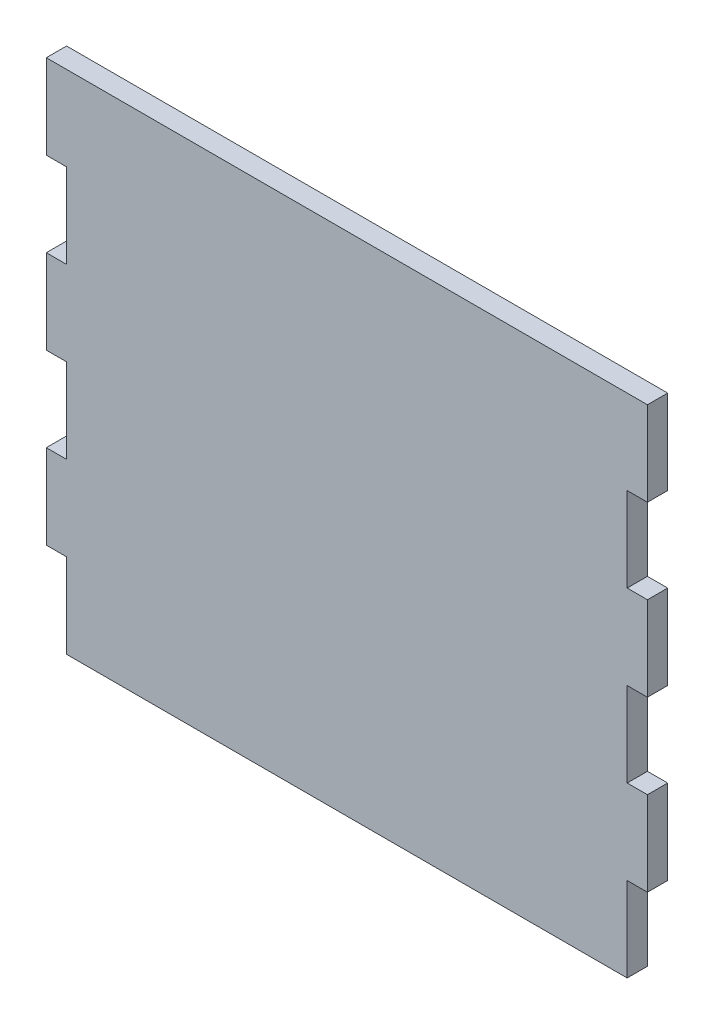
SolidWorks part; units mm, degrees
ref_plane "Front" through (0, 0, 0) normal (0, 0, 1) x (1, 0, 0)
ref_plane "Top" through (0, 0, 0) normal (0, 1, 0) x (1, 0, 0)
ref_plane "Right" through (0, 0, 0) normal (1, 0, 0) x (0, 0, -1)
sketch "Sketch1" plane through (0, 0, 0) normal (0, 0, 1) x (1, 0, 0)
  line L1 (0, 0) -> (-178, 0)
  line L2 (0, 0) -> (0, 150)
  line L3 (0, 150) -> (-178, 150)
  line L4 (-178, 0) -> (-178, 150)
  dimension "D1" = 150
  dimension "D2" = 178
extrude "Boss-Extrude1" add sketch "Sketch1" along normal blind 6
sketch "Sketch2" plane through (0, 0, 6) normal (0, 0, 1) x (1, 0, 0)
  line L0 (-178, 150) -> (-178, 0) construction
  line L1 (-178, 125) -> (-172, 125)
  line L2 (-178, 125) -> (-178, 100)
  line L3 (-178, 100) -> (-172, 100)
  line L4 (-172, 125) -> (-172, 100)
  line L5 (0, 150) -> (-178, 150) construction
  dimension "D1" = 25
  dimension "D2" = 25
  dimension "D3" = 6
extrude "Cut-Extrude1" cut sketch "Sketch2" against normal blind 6
pattern_linear "LPattern1" count 3 spacing 50 along (0, -1, 0) count 2 spacing 172 along (1, 0, 0) of "Cut-Extrude1"
